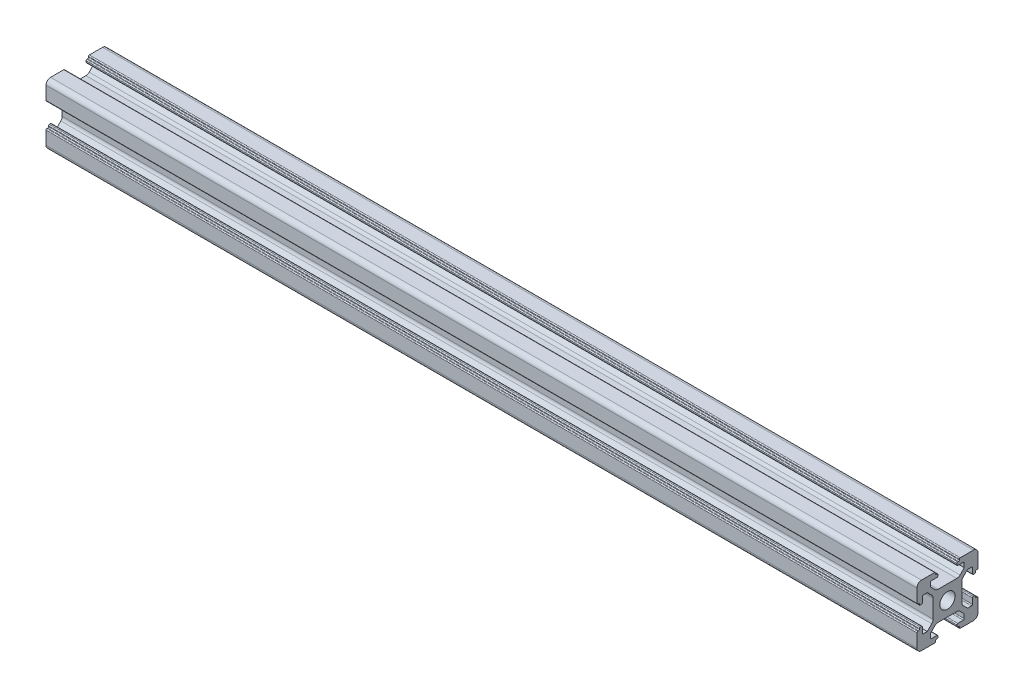
SolidWorks part; units mm, degrees
ref_plane "Front Plane" through (0, 0, 0) normal (0, 0, 1) x (1, 0, 0)
ref_plane "Top Plane" through (0, 0, 0) normal (0, 1, 0) x (1, 0, 0)
ref_plane "Right Plane" through (0, 0, 0) normal (1, 0, 0) x (0, 0, -1)
sketch "Sketch1" plane through (0, 0, 0) normal (1, 0, 0) x (0, 0, -1)
  line L0 (0, 0) -> (0, 50000) construction
  line L1 (0, 0) -> (-50000, 0) construction
  line L2 (10, 4.2) -> (10, 8.5)
  line L3 (9.7, 3.9) -> (9.5, 3.9)
  line L4 (9.2, 3.6) -> (9.2, 3.4)
  line L5 (8.9, 3.1) -> (8.5, 3.1)
  line L6 (8.2, 3.4) -> (8.2, 5.2)
  line L7 (7.9, 5.5) -> (6.6, 5.5)
  line L8 (6.6, 5.5) -> (5.1393, 4.0393)
  line L9 (8.5, 10) -> (4.2, 10)
  line L10 (3.9, 9.7) -> (3.9, 9.5)
  line L11 (3.6, 9.2) -> (3.4, 9.2)
  line L12 (3.1, 8.9) -> (3.1, 8.5)
  line L13 (3.4, 8.2) -> (5.2, 8.2)
  line L14 (5.5, 7.9) -> (5.5, 6.5213)
  line L15 (5.5, 6.5213) -> (4.118, 5.1393)
  line L16 (4.7, 2.9787) -> (4.7, -2.9787)
  line L17 (3.0574, 4.7) -> (-3.0574, 4.7)
  line L18 (-4.7, 2.9787) -> (-4.7, -2.9787)
  line L19 (-5.5, 6.5213) -> (-4.118, 5.1393)
  line L20 (-5.5, 7.9) -> (-5.5, 6.5213)
  line L21 (-3.4, 8.2) -> (-5.2, 8.2)
  line L22 (-3.1, 8.9) -> (-3.1, 8.5)
  line L23 (-3.6, 9.2) -> (-3.4, 9.2)
  line L24 (-3.9, 9.7) -> (-3.9, 9.5)
  line L25 (-8.5, 10) -> (-4.2, 10)
  line L26 (-6.6, 5.5) -> (-5.1393, 4.0393)
  line L27 (-7.9, 5.5) -> (-6.6, 5.5)
  line L28 (-8.2, 3.4) -> (-8.2, 5.2)
  line L29 (-8.9, 3.1) -> (-8.5, 3.1)
  line L30 (-9.2, 3.6) -> (-9.2, 3.4)
  line L31 (-9.7, 3.9) -> (-9.5, 3.9)
  line L32 (-10, 4.2) -> (-10, 8.5)
  line L33 (-10, -4.2) -> (-10, -8.5)
  line L34 (-9.7, -3.9) -> (-9.5, -3.9)
  line L35 (-9.2, -3.6) -> (-9.2, -3.4)
  line L36 (-8.9, -3.1) -> (-8.5, -3.1)
  line L37 (-8.2, -3.4) -> (-8.2, -5.2)
  line L38 (-7.9, -5.5) -> (-6.6, -5.5)
  line L39 (-6.6, -5.5) -> (-5.1393, -4.0393)
  line L40 (-8.5, -10) -> (-4.2, -10)
  line L41 (-3.9, -9.7) -> (-3.9, -9.5)
  line L42 (-3.6, -9.2) -> (-3.4, -9.2)
  line L43 (-3.1, -8.9) -> (-3.1, -8.5)
  line L44 (-3.4, -8.2) -> (-5.2, -8.2)
  line L45 (-5.5, -7.9) -> (-5.5, -6.5213)
  line L46 (-5.5, -6.5213) -> (-4.118, -5.1393)
  line L47 (3.0574, -4.7) -> (-3.0574, -4.7)
  line L48 (5.5, -6.5213) -> (4.118, -5.1393)
  line L49 (5.5, -7.9) -> (5.5, -6.5213)
  line L50 (3.4, -8.2) -> (5.2, -8.2)
  line L51 (3.1, -8.9) -> (3.1, -8.5)
  line L52 (3.6, -9.2) -> (3.4, -9.2)
  line L53 (3.9, -9.7) -> (3.9, -9.5)
  line L54 (8.5, -10) -> (4.2, -10)
  line L55 (6.6, -5.5) -> (5.1393, -4.0393)
  line L56 (7.9, -5.5) -> (6.6, -5.5)
  line L57 (8.2, -3.4) -> (8.2, -5.2)
  line L58 (8.9, -3.1) -> (8.5, -3.1)
  line L59 (9.2, -3.6) -> (9.2, -3.4)
  line L60 (9.7, -3.9) -> (9.5, -3.9)
  line L61 (10, -4.2) -> (10, -8.5)
  circle A0 centre (0, 0) radius 2.5
  arc A1 (10, 8.5) -> (8.5, 10) centre (8.5, 8.5) ccw
  arc A2 (9.7, 3.9) -> (10, 4.2) centre (9.7, 4.2) ccw
  arc A3 (9.5, 3.9) -> (9.2, 3.6) centre (9.5, 3.6) ccw
  arc A4 (9.2, 3.4) -> (8.9, 3.1) centre (8.9, 3.4) cw
  arc A5 (8.5, 3.1) -> (8.2, 3.4) centre (8.5, 3.4) cw
  arc A6 (8.2, 5.2) -> (7.9, 5.5) centre (7.9, 5.2) ccw
  arc A7 (5.2, 8.2) -> (5.5, 7.9) centre (5.2, 7.9) cw
  arc A8 (3.1, 8.5) -> (3.4, 8.2) centre (3.4, 8.5) ccw
  arc A9 (3.4, 9.2) -> (3.1, 8.9) centre (3.4, 8.9) ccw
  arc A10 (4.2, 10) -> (3.9, 9.7) centre (4.2, 9.7) ccw
  arc A11 (3.9, 9.5) -> (3.6, 9.2) centre (3.6, 9.5) cw
  arc A12 (4.7, 2.9787) -> (5.1393, 4.0393) centre (6.2, 2.9787) cw
  arc A13 (3.0574, 4.7) -> (4.118, 5.1393) centre (3.0574, 6.2) ccw
  arc A14 (-3.0574, 4.7) -> (-4.118, 5.1393) centre (-3.0574, 6.2) cw
  arc A15 (-4.7, 2.9787) -> (-5.1393, 4.0393) centre (-6.2, 2.9787) ccw
  arc A16 (-3.9, 9.5) -> (-3.6, 9.2) centre (-3.6, 9.5) ccw
  arc A17 (-4.2, 10) -> (-3.9, 9.7) centre (-4.2, 9.7) cw
  arc A18 (-3.4, 9.2) -> (-3.1, 8.9) centre (-3.4, 8.9) cw
  arc A19 (-3.1, 8.5) -> (-3.4, 8.2) centre (-3.4, 8.5) cw
  arc A20 (-5.2, 8.2) -> (-5.5, 7.9) centre (-5.2, 7.9) ccw
  arc A21 (-8.2, 5.2) -> (-7.9, 5.5) centre (-7.9, 5.2) cw
  arc A22 (-8.5, 3.1) -> (-8.2, 3.4) centre (-8.5, 3.4) ccw
  arc A23 (-9.2, 3.4) -> (-8.9, 3.1) centre (-8.9, 3.4) ccw
  arc A24 (-9.5, 3.9) -> (-9.2, 3.6) centre (-9.5, 3.6) cw
  arc A25 (-9.7, 3.9) -> (-10, 4.2) centre (-9.7, 4.2) cw
  arc A26 (-10, 8.5) -> (-8.5, 10) centre (-8.5, 8.5) cw
  arc A27 (-10, -8.5) -> (-8.5, -10) centre (-8.5, -8.5) ccw
  arc A28 (-9.7, -3.9) -> (-10, -4.2) centre (-9.7, -4.2) ccw
  arc A29 (-9.5, -3.9) -> (-9.2, -3.6) centre (-9.5, -3.6) ccw
  arc A30 (-9.2, -3.4) -> (-8.9, -3.1) centre (-8.9, -3.4) cw
  arc A31 (-8.5, -3.1) -> (-8.2, -3.4) centre (-8.5, -3.4) cw
  arc A32 (-8.2, -5.2) -> (-7.9, -5.5) centre (-7.9, -5.2) ccw
  arc A33 (-5.2, -8.2) -> (-5.5, -7.9) centre (-5.2, -7.9) cw
  arc A34 (-3.1, -8.5) -> (-3.4, -8.2) centre (-3.4, -8.5) ccw
  arc A35 (-3.4, -9.2) -> (-3.1, -8.9) centre (-3.4, -8.9) ccw
  arc A36 (-4.2, -10) -> (-3.9, -9.7) centre (-4.2, -9.7) ccw
  arc A37 (-3.9, -9.5) -> (-3.6, -9.2) centre (-3.6, -9.5) cw
  arc A38 (-4.7, -2.9787) -> (-5.1393, -4.0393) centre (-6.2, -2.9787) cw
  arc A39 (-3.0574, -4.7) -> (-4.118, -5.1393) centre (-3.0574, -6.2) ccw
  arc A40 (3.0574, -4.7) -> (4.118, -5.1393) centre (3.0574, -6.2) cw
  arc A41 (4.7, -2.9787) -> (5.1393, -4.0393) centre (6.2, -2.9787) ccw
  arc A42 (3.9, -9.5) -> (3.6, -9.2) centre (3.6, -9.5) ccw
  arc A43 (4.2, -10) -> (3.9, -9.7) centre (4.2, -9.7) cw
  arc A44 (3.4, -9.2) -> (3.1, -8.9) centre (3.4, -8.9) cw
  arc A45 (3.1, -8.5) -> (3.4, -8.2) centre (3.4, -8.5) cw
  arc A46 (5.2, -8.2) -> (5.5, -7.9) centre (5.2, -7.9) ccw
  arc A47 (8.2, -5.2) -> (7.9, -5.5) centre (7.9, -5.2) cw
  arc A48 (8.5, -3.1) -> (8.2, -3.4) centre (8.5, -3.4) ccw
  arc A49 (9.2, -3.4) -> (8.9, -3.1) centre (8.9, -3.4) ccw
  arc A50 (9.5, -3.9) -> (9.2, -3.6) centre (9.5, -3.6) cw
  arc A51 (9.7, -3.9) -> (10, -4.2) centre (9.7, -4.2) cw
  arc A52 (10, -8.5) -> (8.5, -10) centre (8.5, -8.5) cw
  point P24 (10, 10)
  point P41 (3.1, 9.2)
  point P44 (3.9, 10)
  point P47 (2.4302, 3.4515)
  point P52 (2.8319, 3.8532)
  point P94 (4.7, 0)
  point P95 (0, 4.7)
  point P175 (0, -4.7)
  point P176 (-4.7, 0)
  dimension "D1" = 5
  dimension "D15" = 1.5
  dimension "D16" = 0.3
  dimension "D19" = 1.5
  dimension "D2" = 20
  dimension "D3" = 1.8
  dimension "D4" = 6.2
  dimension "D5" = 3.4
  dimension "D6" = 11
  dimension "D7" = 6.1
  dimension "D8" = 1.5
  dimension "D9" = 20
  dimension "D10" = 6.1
  dimension "D11" = 6.2
  dimension "D12" = 11
  dimension "D13" = 45
  dimension "D14" = 1.8
  dimension "D17" = 3.5
  dimension "D18" = 3.5
extrude "Boss-Extrude2" add sketch "Sketch1" along normal mid plane 285
